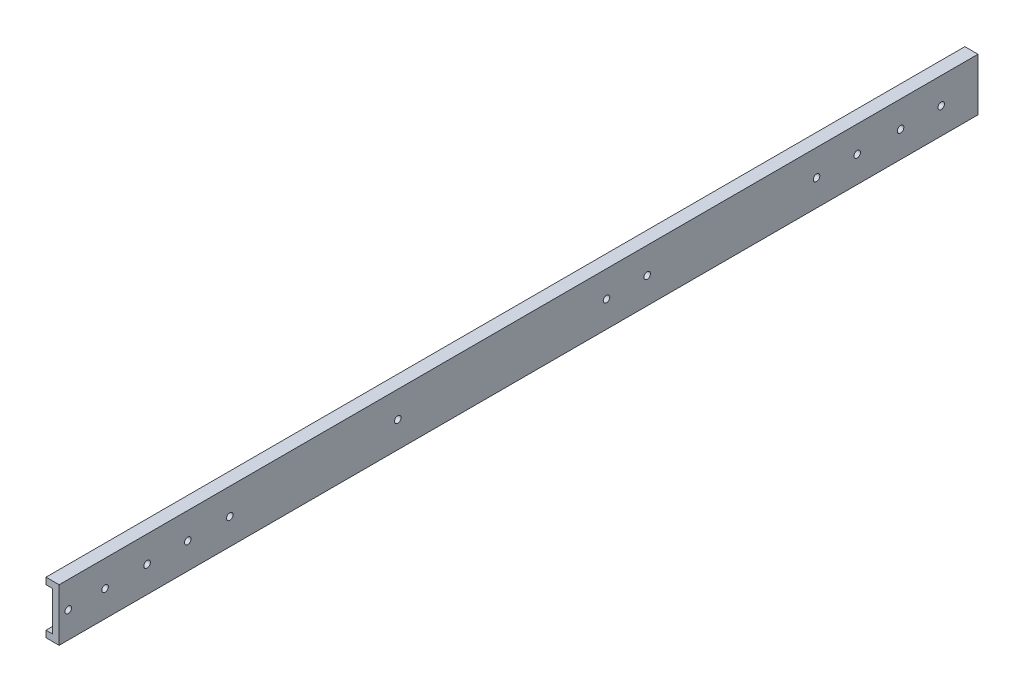
SolidWorks part; units mm, degrees
ref_plane "Front Plane" through (0, 0, 0) normal (0, 0, 1) x (1, 0, 0)
ref_plane "Top Plane" through (0, 0, 0) normal (0, 1, 0) x (1, 0, 0)
ref_plane "Right Plane" through (0, 0, 0) normal (1, 0, 0) x (0, 0, -1)
sketch "Sketch1" plane through (0, 0, 0) normal (0, 0, 1) x (1, 0, 0)
  line L1 (0, 0) -> (10, 0)
  line L2 (0, 0) -> (0, 40)
  line L3 (0, 40) -> (10, 40)
  line L4 (10, 0) -> (10, 40)
  dimension "D1" = 10
  dimension "D2" = 40
extrude "Boss-Extrude1" add sketch "Sketch1" along normal blind 700
sketch "Sketch2" plane through (0, 0, 700) normal (0, 0, 1) x (1, 0, 0)
  line L0 (0, 40) -> (0, 0) construction
  line L1 (0, 35) -> (5, 35)
  line L2 (0, 35) -> (0, 5)
  line L3 (0, 5) -> (5, 5)
  line L4 (5, 35) -> (5, 5)
  line L5 (0, 0) -> (10, 0) construction
  dimension "D1" = 5
  dimension "D2" = 30
  dimension "D3" = 5
extrude "Cut-Extrude1" cut sketch "Sketch2" against normal through all both and the other way through all
sketch "Sketch3" plane through (10, 0, 0) normal (1, 0, 0) x (0, 0, -1)
  line L0 (-700, 20) -> (0, 20) construction
  line L1 (-700, 0) -> (-700, 40) construction
  line L2 (0, 0) -> (0, 40) construction
  circle A0 centre (-693, 20) radius 2.5
  circle A1 centre (-665, 20) radius 2.5
  circle A2 centre (-633, 20) radius 2.5
  circle A3 centre (-602, 20) radius 2.5
  circle A4 centre (-570, 20) radius 2.5
  circle A5 centre (-442, 20) radius 2.5
  circle A6 centre (-283, 20) radius 2.5
  circle A7 centre (-252, 20) radius 2.5
  circle A8 centre (-123, 20) radius 2.5
  circle A9 centre (-92, 20) radius 2.5
  circle A10 centre (-59, 20) radius 2.5
  circle A11 centre (-28, 20) radius 2.5
  dimension "D5" = 130
  dimension "D6" = 258
  dimension "D8" = 448
  dimension "D9" = 577
  dimension "D10" = 608
  dimension "D13" = 5
  dimension "D1" = 7
  dimension "D2" = 35
  dimension "D3" = 67
  dimension "D4" = 98
  dimension "D7" = 417
  dimension "D11" = 641
  dimension "D12" = 672
extrude "Cut-Extrude2" cut sketch "Sketch3" against normal through all
